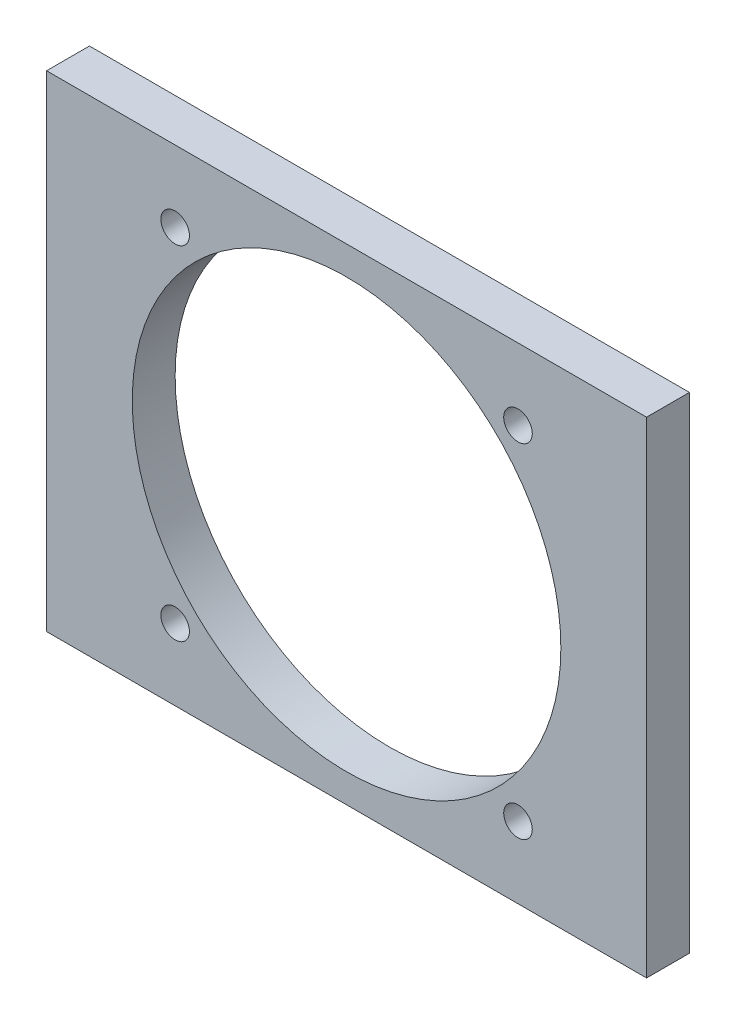
SolidWorks part; units mm, degrees
ref_plane "Ön Düzlem" through (0, 0, 0) normal (0, 0, 1) x (1, 0, 0)
ref_plane "Üst Düzlem" through (0, 0, 0) normal (0, 1, 0) x (1, 0, 0)
ref_plane "Sağ Düzlem" through (0, 0, 0) normal (1, 0, 0) x (0, 0, -1)
sketch "Sketch1" plane through (0, 0, 0) normal (0, 0, 1) x (1, 0, 0)
  line L1 (-105, -85) -> (105, -85)
  line L2 (-105, -85) -> (-105, 85)
  line L3 (-105, 85) -> (105, 85)
  line L4 (105, -85) -> (105, 85)
  line L5 (-105, -85) -> (105, 85) construction
  line L6 (-105, 85) -> (105, -85) construction
  point P0 (0, 0)
  dimension "D1" = 170
  dimension "D2" = 210
extrude "Boss-Extrude1" add sketch "Sketch1" along normal blind 15
sketch "Sketch2" plane through (0, 0, 15) normal (0, 0, 1) x (1, 0, 0)
  line L1 (-60, -60) -> (60, -60) construction
  line L2 (-60, -60) -> (-60, 60) construction
  line L3 (-60, 60) -> (60, 60) construction
  line L4 (60, -60) -> (60, 60) construction
  line L5 (-60, -60) -> (60, 60) construction
  line L6 (-60, 60) -> (60, -60) construction
  circle A4 centre (0, 0) radius 75
  circle A5 centre (-60, 60) radius 5
  circle A6 centre (60, 60) radius 5
  circle A7 centre (60, -60) radius 5
  circle A8 centre (-60, -60) radius 5
  dimension "D1" = 150
  dimension "D3" = 10
  dimension "D2" = 120
extrude "Cut-Extrude1" cut sketch "Sketch2" against normal up to surface (15 mm away) up to face at (0, 0, 0)
